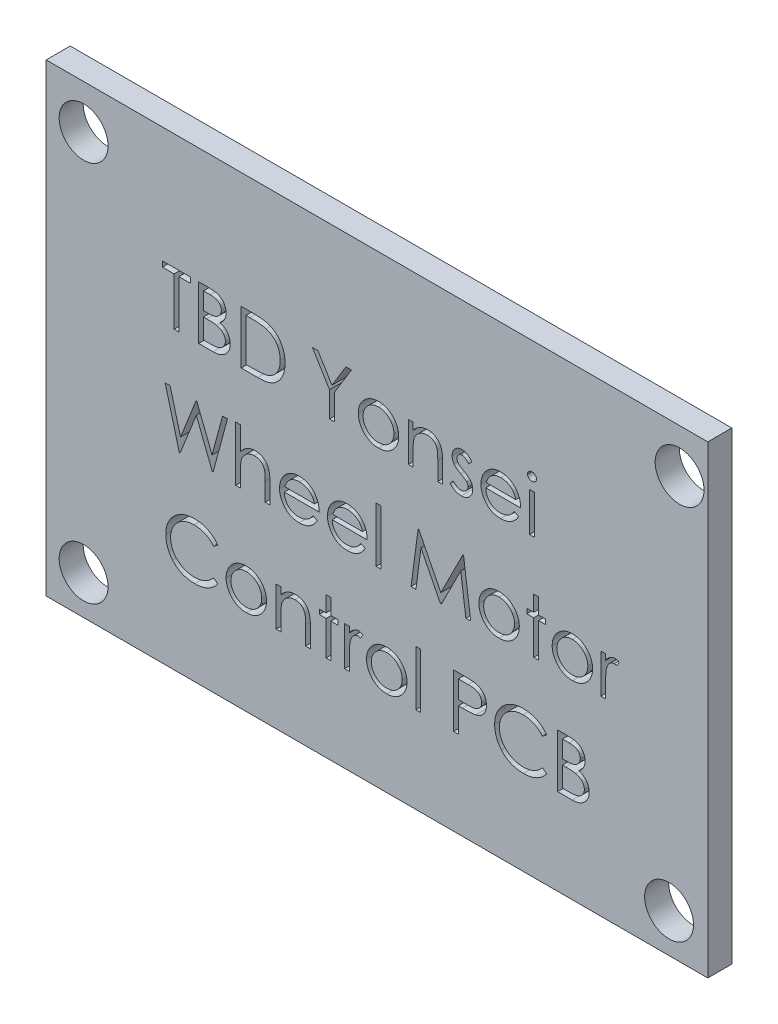
SolidWorks part; units mm, degrees
ref_plane "Front Plane" through (0, 0, 0) normal (0, 0, 1) x (1, 0, 0)
ref_plane "Top Plane" through (0, 0, 0) normal (0, 1, 0) x (1, 0, 0)
ref_plane "Right Plane" through (0, 0, 0) normal (1, 0, 0) x (0, 0, -1)
sketch "Sketch1" plane through (0, 0, 0) normal (0, 0, 1) x (1, 0, 0)
  line L0 (0, 0) -> (0, 30.414)
  line L1 (0, 30.414) -> (43.336, 30.414)
  line L2 (43.336, 30.414) -> (43.336, 0)
  line L3 (43.336, 0) -> (0, 0)
  circle A0 centre (41.49, 27.55) radius 1.6
  circle A1 centre (40.8, 2.55) radius 1.6
  circle A2 centre (2.45, 2.55) radius 1.6
  circle A3 centre (40.8, 2.55) radius 1.6
  circle A4 centre (2.45, 27.55) radius 1.6
  dimension "D1" = 43.336
  dimension "D2" = 30.414
extrude "Boss-Extrude1" add sketch "Sketch1" against normal blind 1.575 contours L3 L2 L1 L0 A4 A2 A1 A0
sketch "Sketch3" plane through (0, 0, 0) normal (0, 0, 1) x (1, 0, 0)
  text T0 "TBD Yonsei\r\nWheel Motor\r\nControl PCB"
extrude "Cut-Extrude2" cut sketch "Sketch3" against normal through all
